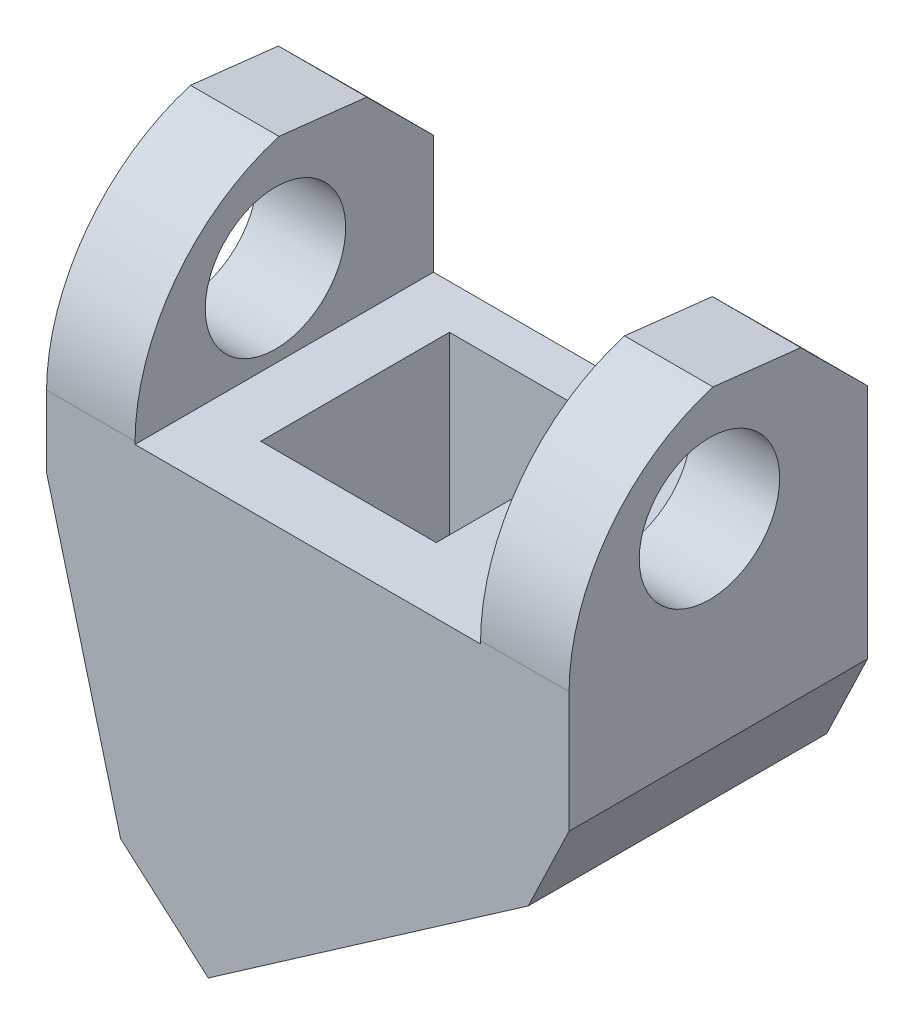
SolidWorks part; units mm, degrees
ref_plane "Front Plane" through (0, 0, 0) normal (0, 0, 1) x (1, 0, 0)
ref_plane "Top Plane" through (0, 0, 0) normal (0, 1, 0) x (1, 0, 0)
ref_plane "Right Plane" through (0, 0, 0) normal (1, 0, 0) x (0, 0, -1)
sketch "Sketch1" plane through (0, 0, 0) normal (0, 0, 1) x (1, 0, 0)
  line L0 (-13.2171, 28.3371) -> (-8.1771, 28.3371)
  line L1 (-8.1771, 28.3371) -> (-8.1771, 17.2371)
  line L2 (-8.1771, 17.2371) -> (11.5056, 17.2371)
  line L3 (11.5056, 17.2371) -> (11.5056, 28.3371)
  line L4 (11.5056, 28.3371) -> (16.5456, 28.3371)
  line L5 (16.5456, 28.3371) -> (16.5456, 10.5166)
  line L6 (16.5456, 10.5166) -> (14.2254, 5.6737)
  line L7 (14.2254, 5.6737) -> (-4.0039, -6.9965)
  line L8 (-4.0039, -6.9965) -> (-9, -2.6229)
  line L9 (-9, -2.6229) -> (-13.2171, 13.3371)
  line L10 (-13.2171, 13.3371) -> (-13.2171, 28.3371)
  dimension "D1" = 5.04
  dimension "D2" = 5.04
  dimension "D3" = 15
  dimension "D4" = 15.96
  dimension "D5" = 6.64
  dimension "D6" = 22.2
  dimension "D7" = 104
  dimension "D8" = 146
  dimension "D9" = 5.37
  dimension "D10" = 150.4
  dimension "D11" = 11.1
extrude "Boss-Extrude1" add sketch "Sketch1" along normal blind 17
sketch "Sketch4" plane through (-8.1771, 0, 0) normal (1, 0, 0) x (0, 0, -1)
  line L0 (-17, 17.2371) -> (0, 17.2371)
  line L1 (0, 17.2371) -> (0, 23.9971)
  line L2 (0, 17.2371) -> (0, 28.3371) construction
  line L3 (0, 23.9971) -> (-3.7972, 27.7745)
  line L4 (-3.7972, 27.7745) -> (-8.7972, 28.3371)
  line L5 (-17, 28.3371) -> (0, 28.3371) construction
  arc A0 (-8.7972, 28.3371) -> (-17, 17.2371) centre (-5.5003, 17.3199) ccw
  line M6 (0, 17.2371) -> (0, 28.3371)
  line M7 (0, 28.3371) -> (-17, 28.3371)
  line M8 (-17, 28.3371) -> (-17, 17.2371)
  dimension "D5" = 11.5
  dimension "D1" = 6.76
  dimension "D2" = 134.85
  dimension "D3" = 141.57
  dimension "D4" = 5
extrude "Cut-Extrude3" cut sketch "Sketch4" against normal blind 17 and the other way blind 27 contours A0 M7 M8 | L4 L3 M6 M7
sketch "Sketch5" plane through (1.9747, -2.8411, 0) normal (0.5707, -0.8211, 0) x (0.8211, 0.5707, 0)
  line L0 (-7.2808, 17) -> (-7.2808, 0) construction
  line L1 (-3.2808, 13.26) -> (6.1892, 13.26)
  line L2 (-3.2808, 13.26) -> (-3.2808, 2.51)
  line L3 (-3.2808, 2.51) -> (6.1892, 2.51)
  line L4 (6.1892, 13.26) -> (6.1892, 2.51)
  line L5 (-7.2808, 17) -> (14.9192, 17) construction
  dimension "D1" = 4
  dimension "D2" = 3.74
  dimension "D3" = 10.75
  dimension "D4" = 9.47
ref_plane "Plane1" through (0, 0, 10) normal (0, 0, 1) x (1, 0, 0)
sketch "Sketch6" plane through (0, 0, 10) normal (0, 0, 1) x (1, 0, 0)
  line L0 (0.8515, -3.6217) -> (-5.9203, 2.3063)
  line L1 (-0.7193, -4.7135) -> (7.0569, 0.6913) construction
  line L2 (-9, -2.6229) -> (-4.0039, -6.9965) construction
  dimension "D1" = 9
sweep "Cut-Sweep1" cut profiles "Sketch5" path "Sketch6"
sketch "Sketch7" plane through (0, 17.2371, 0) normal (0, 1, 0) x (1, 0, 0)
  line L0 (-13.2171, -3.7972) -> (-13.2171, -8.7972) construction
  line L1 (-4.7571, -2.51) -> (5.2429, -2.51)
  line L2 (-4.7571, -2.51) -> (-4.7571, -13.26)
  line L3 (-4.7571, -13.26) -> (5.2429, -13.26)
  line L4 (5.2429, -2.51) -> (5.2429, -13.26)
  line L5 (11.5056, -17) -> (-8.1771, -17) construction
  dimension "D1" = 8.46
  dimension "D2" = 10.75
  dimension "D3" = 3.74
  dimension "D4" = 10
extrude "Cut-Extrude4" cut sketch "Sketch7" against normal up to surface (27.17 mm away)
sketch "Sketch8" plane through (-13.2171, 0, 0) normal (-1, 0, 0) x (0, 0, 1)
  line L0 (17, 13.3371) -> (0, 13.3371) construction
  line L1 (17, 17.4026) -> (17, 13.3371) construction
  circle A0 centre (9, 21.9371) radius 4
  dimension "D1" = 8
  dimension "D2" = 8.6
  dimension "D3" = 8
extrude "Cut-Extrude5" cut sketch "Sketch8" against normal blind 37
